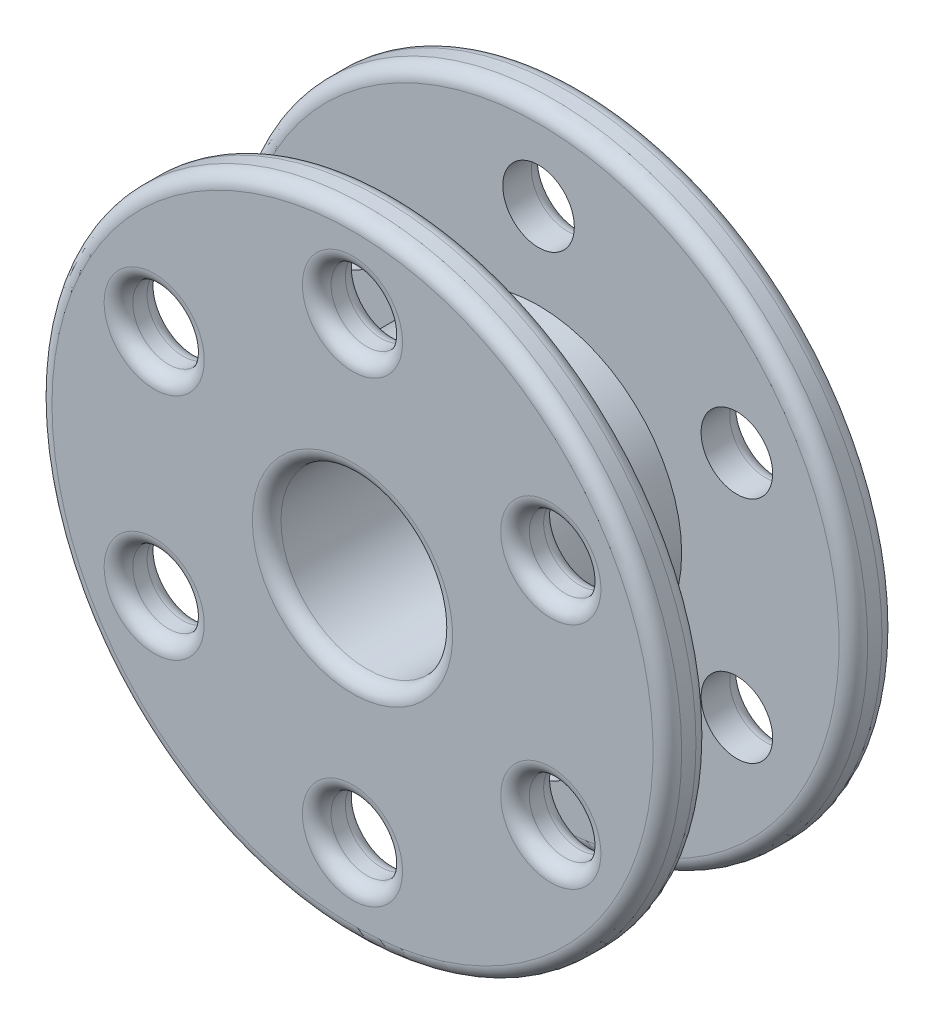
SolidWorks part; units mm, degrees
ref_plane "Front Plane" through (0, 0, 0) normal (0, 0, 1) x (1, 0, 0)
ref_plane "Top Plane" through (0, 0, 0) normal (0, 1, 0) x (1, 0, 0)
ref_plane "Right Plane" through (0, 0, 0) normal (1, 0, 0) x (0, 0, -1)
sketch "Sketch1" plane through (0, 0, 0) normal (1, 0, 0) x (0, 0, -1)
  line L0 (-5, 10) -> (5, 10)
  line L1 (5, 10) -> (5, 22)
  line L2 (5, 22) -> (8, 22)
  line L3 (8, 22) -> (8, 6)
  line L4 (8, 6) -> (-8, 6)
  line L5 (-8, 6) -> (-8, 22)
  line L6 (-8, 22) -> (-5, 22)
  line L7 (-5, 22) -> (-5, 10)
  line L8 (-8, 0) -> (8, 0) construction
  point P11 (0, 6)
  point P12 (0, 10)
  point P13 (0, 0)
  dimension "D1" = 6
  dimension "D2" = 10
  dimension "D3" = 22
  dimension "D4" = 16
  dimension "D5" = 3
revolve "Revolve1" add sketch "Sketch1" angle 360 about L8
sketch "Sketch2" plane through (0, 0, 8) normal (0, 0, 1) x (1, 0, 0)
  circle A0 centre (0, 16) radius 2.5
  circle A1 centre (13.8564, 8) radius 2.5
  circle A2 centre (13.8564, -8) radius 2.5
  circle A3 centre (0, -16) radius 2.5
  circle A4 centre (-13.8564, -8) radius 2.5
  circle A5 centre (-13.8564, 8) radius 2.5
  point P15 (0, 0)
  dimension "D1" = 5
  dimension "D2" = 16
  dimension "D3" = 6
extrude "Cut-Extrude1" cut sketch "Sketch2" against normal through all both and the other way through all contours A0 | A1 | A2 | A3 | A4 | A5
fillet "Fillet1" radius 1 25 edges at (22, 0, 8) (22, 0, -5) (6, 0, -8) (22, 0, -8) (16.3564, 8, -8) (16.3564, -8, -8) (2.5, -16, -8) (-11.3564, -8, -8) (-11.3564, 8, -8) (2.5, 16, -8) (6, 0, 8) (11.3564, 8, 8) (11.3564, -8, 8) (-2.5, -16, 8) (-16.3564, -8, 8) (-16.3564, 8, 8) (-2.5, 16, 8) (10, 0, 5) (22, 0, 5) (16.3564, 8, 5) (16.3564, -8, 5) (2.5, -16, 5) (-11.3564, -8, 5) (-11.3564, 8, 5) (2.5, 16, 5)
